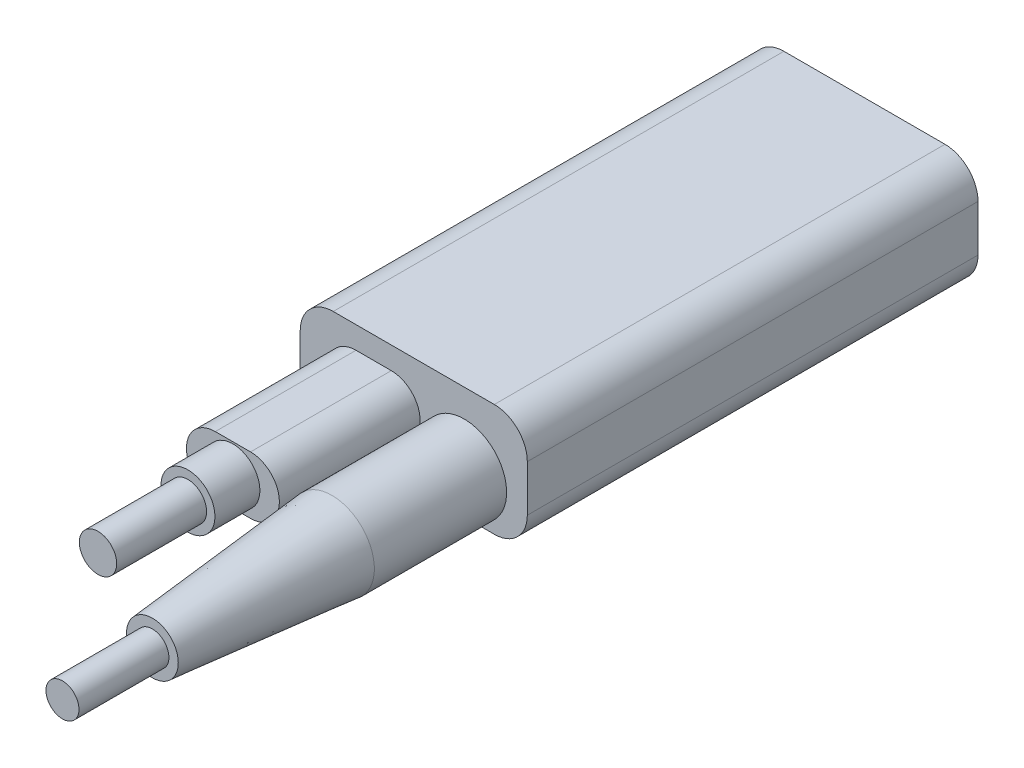
SolidWorks part; units mm, degrees
ref_plane "Front Plane" through (0, 0, 0) normal (0, 0, 1) x (1, 0, 0)
ref_plane "Top Plane" through (0, 0, 0) normal (0, 1, 0) x (1, 0, 0)
ref_plane "Right Plane" through (0, 0, 0) normal (1, 0, 0) x (0, 0, -1)
sketch "Sketch1" plane through (0, 0, 0) normal (0, 0, 1) x (1, 0, 0)
  line L1 (-12.625, -6.25) -> (12.625, -6.25)
  line L2 (-12.625, -6.25) -> (-12.625, 6.25)
  line L3 (-12.625, 6.25) -> (12.625, 6.25)
  line L4 (12.625, -6.25) -> (12.625, 6.25)
  line L5 (-12.625, -6.25) -> (12.625, 6.25) construction
  line L6 (-12.625, 6.25) -> (12.625, -6.25) construction
  point P0 (0, 0)
  dimension "D1" = 12.5
  dimension "D2" = 25.25
extrude "Boss-Extrude1" add sketch "Sketch1" along normal mid plane 50.11
sketch "Sketch2" plane through (0, 0, -25.055) normal (0, 0, -1) x (-1, 0, 0)
  line L0 (0, 0) -> (0, -1.17) construction
  line L1 (-7.25, -4.02) -> (7.25, -4.02)
  line L2 (-7.25, -4.02) -> (-7.25, 1.68)
  line L3 (-7.25, 1.68) -> (7.25, 1.68)
  line L4 (7.25, -4.02) -> (7.25, 1.68)
  line L5 (-7.25, -4.02) -> (7.25, 1.68) construction
  line L6 (-7.25, 1.68) -> (7.25, -4.02) construction
  line L7 (-12.625, 6.25) -> (12.625, 6.25) construction
  point P0 (0, -1.17)
  dimension "D1" = 4.57
  dimension "D2" = 14.5
  dimension "D3" = 5.7
extrude "Cut-Extrude1" cut sketch "Sketch2" against normal blind 10
sketch "Sketch3" plane through (0, 0, 25.055) normal (0, 0, 1) x (1, 0, 0)
  line L0 (-6.42, 0.575) -> (-2.5, 0.575) construction
  line L5 (-6.42, 3.78) -> (-2.5, 3.78)
  line L6 (-6.42, -2.63) -> (-2.5, -2.63)
  line L7 (-12.625, 6.25) -> (-12.625, -6.25) construction
  line L8 (-12.625, -6.25) -> (12.625, -6.25) construction
  arc A1 (-6.42, 3.78) -> (-6.42, -2.63) centre (-6.42, 0.575) ccw
  arc A2 (-2.5, -2.63) -> (-2.5, 3.78) centre (-2.5, 0.575) ccw
  point P2 (-4.46, 0.575)
  point P5 (-9.625, 0.575)
  point P6 (0.705, 0.575)
  dimension "D1" = 10.33
  dimension "D2" = 6.41
  dimension "D3" = 3
  dimension "D4" = 3.62
extrude "Boss-Extrude2" add sketch "Sketch3" along normal blind 15.65
sketch "Sketch4" plane through (0, 0, 25.055) normal (0, 0, 1) x (1, 0, 0)
  line L0 (-12.625, -6.25) -> (12.625, -6.25) construction
  line L1 (10.325, -1.535) -> (12.625, -1.535) construction
  line L2 (12.625, -6.25) -> (12.625, 6.25) construction
  circle A0 centre (5.61, -1.535) radius 4.715
  dimension "D1" = 9.43
  dimension "D2" = 2.3
extrude "Boss-Extrude3" add sketch "Sketch4" along normal blind 14.71
ref_plane "Plane1" through (0, 0, 59.725) normal (0, 0, 1) x (1, 0, 0)
sketch "Sketch5" plane through (0, 0, 59.725) normal (0, 0, 1) x (1, 0, 0)
  circle A0 centre (5.61, -1.535) radius 2.875
  circle A1 centre (5.61, -1.535) radius 4.715 construction
  dimension "D1" = 5.75
loft "Loft1" add profiles "Sketch5" section face at (10.325, -1.535, 39.765) section "Sketch5"
sketch "Sketch6" plane through (0, 0, 59.725) normal (0, 0, 1) x (1, 0, 0)
  circle A0 centre (5.61, -1.535) radius 1.835
  dimension "D1" = 3.67
extrude "Boss-Extrude4" add sketch "Sketch6" along normal blind 10
sketch "Sketch7" plane through (0, 0, 40.705) normal (0, 0, 1) x (1, 0, 0)
  line L0 (-9.625, 0.575) -> (0.705, 0.575) construction
  circle A0 centre (-4.46, 0.575) radius 3
  arc A1 (-6.42, 3.78) -> (-6.42, -2.63) centre (-6.42, 0.575) ccw construction
  arc A2 (-2.5, -2.63) -> (-2.5, 3.78) centre (-2.5, 0.575) ccw construction
  dimension "D1" = 6
extrude "Boss-Extrude5" add sketch "Sketch7" along normal blind 5
sketch "Sketch8" plane through (0, 0, 45.705) normal (0, 0, 1) x (1, 0, 0)
  circle A0 centre (-4.46, 0.575) radius 2.075
  dimension "D1" = 4.15
extrude "Boss-Extrude6" add sketch "Sketch8" along normal blind 10
fillet "Fillet1" radius 3.67 4 edges at (12.625, -6.25, 0) (12.625, 6.25, 0) (-12.625, -6.25, 0) (-12.625, 6.25, 0)
